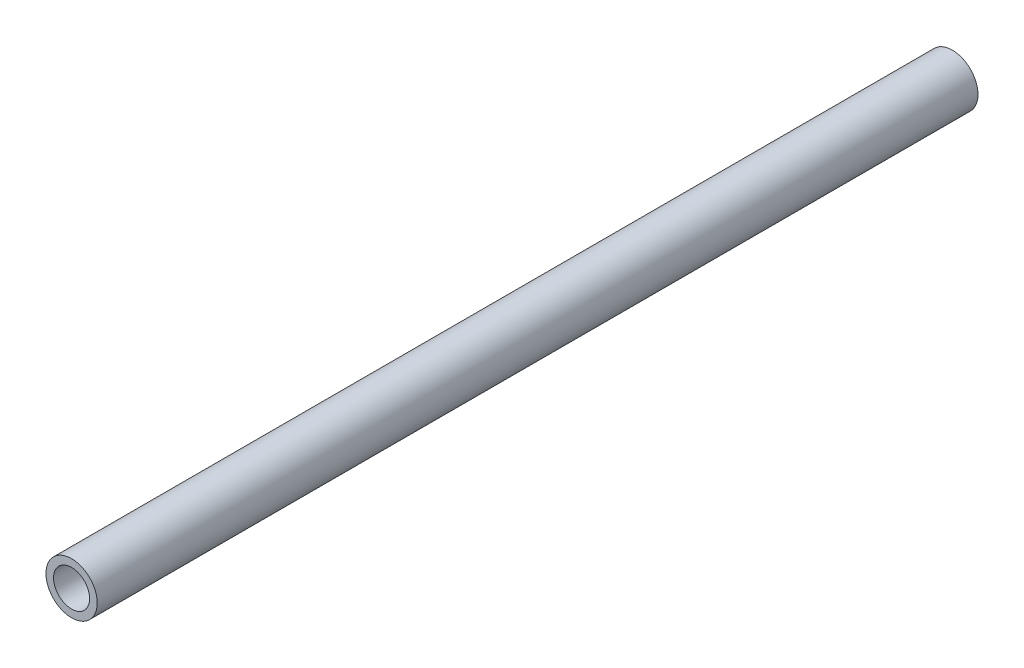
SolidWorks part; units mm, degrees
material "Galvanized Steel"
ref_plane "Front Plane" through (0, 0, 0) normal (0, 0, 1) x (1, 0, 0)
ref_plane "Top Plane" through (0, 0, 0) normal (0, 1, 0) x (1, 0, 0)
ref_plane "Right Plane" through (0, 0, 0) normal (1, 0, 0) x (0, 0, -1)
sketch "Sketch1" plane through (0, 0, 0) normal (0, 0, 1) x (1, 0, 0)
  circle A0 centre (351.5, -19) radius 13.5
  circle A1 centre (351.5, -19) radius 9.5
  circle A2 centre (351.5, -19) radius 14 construction
  dimension "D1" = 27
  dimension "D2" = 19
extrude "Boss-Extrude1" add sketch "Sketch1" along normal up to surface (464 mm away)
